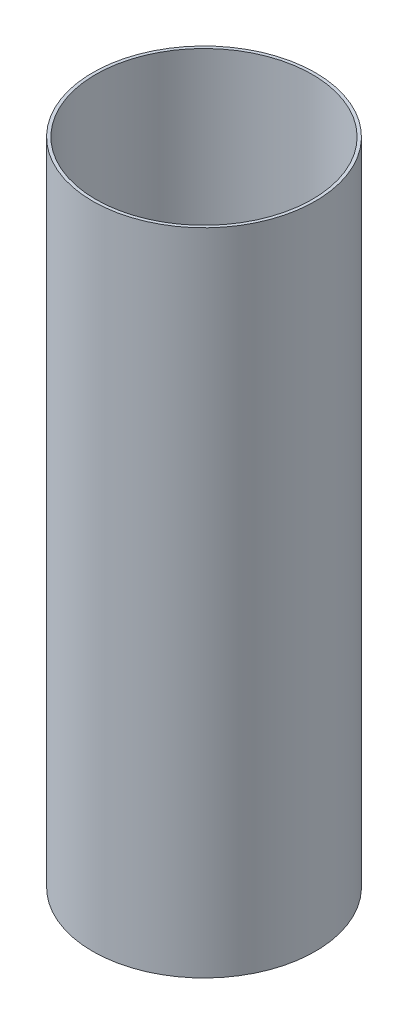
SolidWorks part; units mm, degrees
ref_plane "Front Plane" through (0, 0, 0) normal (0, 0, 1) x (1, 0, 0)
ref_plane "Top Plane" through (0, 0, 0) normal (0, 1, 0) x (1, 0, 0)
ref_plane "Right Plane" through (0, 0, 0) normal (1, 0, 0) x (0, 0, -1)
sketch "Sketch1" plane through (0, 0, 0) normal (0, 1, 0) x (1, 0, 0)
  circle A0 centre (0, 0) radius 76.2
  circle A1 centre (0, 0) radius 78.359
  dimension "D1" = 152.4
  dimension "D2" = 156.718
extrude "Boss-Extrude1" add sketch "Sketch1" along normal blind 457.2
equation "\"Length\"= 18"
equation "\"D1@Boss-Extrude1\"=\"Length\""
